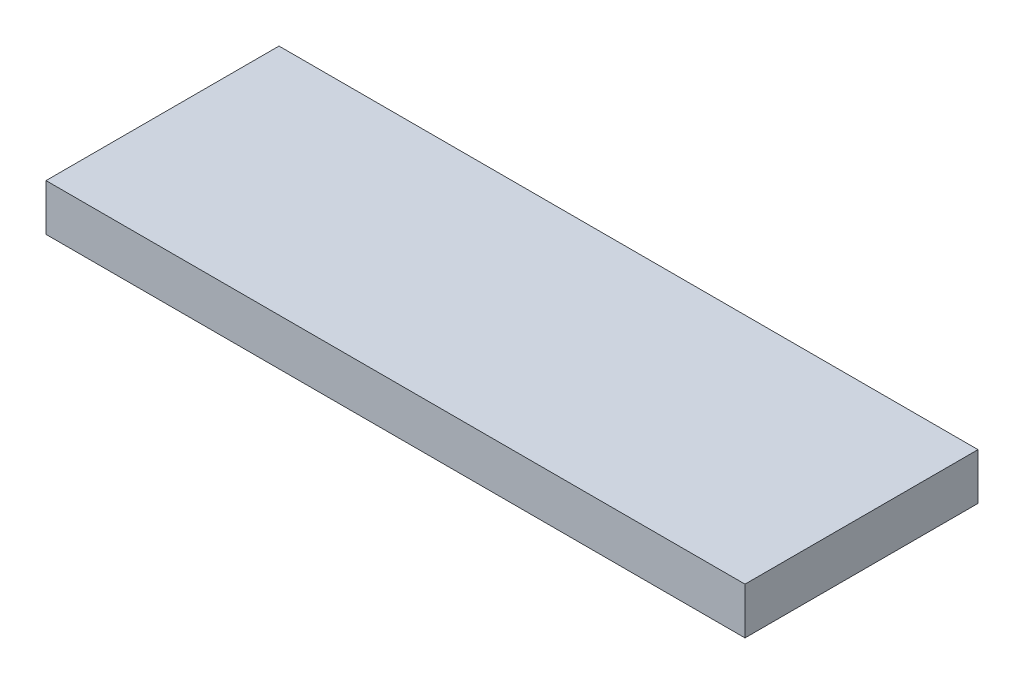
SolidWorks part; units mm, degrees
ref_plane "前视基准面" through (0, 0, 0) normal (0, 0, 1) x (1, 0, 0)
ref_plane "上视基准面" through (0, 0, 0) normal (0, 1, 0) x (1, 0, 0)
ref_plane "右视基准面" through (0, 0, 0) normal (1, 0, 0) x (0, 0, -1)
other "Configuration Table"
sketch "草图1" plane through (0, 0, 0) normal (0, 1, 0) x (1, 0, 0)
  line L1 (-20.4231, 11.8269) -> (24.5769, 11.8269)
  line L2 (-20.4231, 11.8269) -> (-20.4231, -3.1731)
  line L3 (-20.4231, -3.1731) -> (24.5769, -3.1731)
  line L4 (24.5769, 11.8269) -> (24.5769, -3.1731)
  dimension "D1" = 15
  dimension "D2" = 45
extrude "凸台-拉伸1" add sketch "草图1" along normal blind 3
